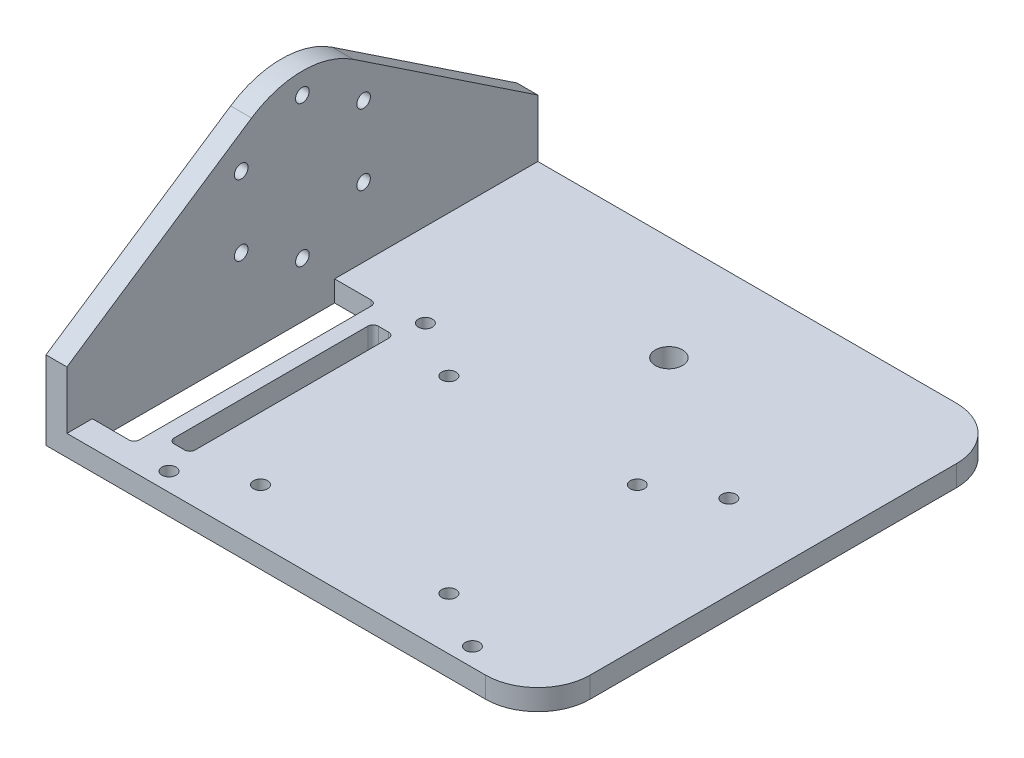
SolidWorks part; units mm, degrees
material "3.1325 (EN-AW 2017A)"
ref_plane "前视基准面" through (0, 0, 0) normal (0, 0, 1) x (1, 0, 0)
ref_plane "上视基准面" through (0, 0, 0) normal (0, 1, 0) x (1, 0, 0)
ref_plane "右视基准面" through (0, 0, 0) normal (1, 0, 0) x (0, 0, -1)
other "Configuration Table"
sketch "草图3" plane through (0, 0, 0) normal (0, 1, 0) x (1, 0, 0)
  line L1 (-45, -45) -> (45, -45)
  line L2 (-45, -45) -> (-45, 45)
  line L3 (-45, 45) -> (45, 45)
  line L4 (45, -45) -> (45, 45)
  line L5 (-45, -45) -> (45, 45) construction
  line L6 (-45, 45) -> (45, -45) construction
  point P0 (0, 0)
  dimension "D1" = 90
  dimension "D2" = 90
extrude "凸台-拉伸3" add sketch "草图3" along normal blind 4
sketch "草图4" plane through (-45, 0, 0) normal (-1, 0, 0) x (0, 0, 1)
  line L1 (-45, 4) -> (45, 4) construction
  line L4 (-45, 4) -> (-45, 15)
  line L5 (-45, 15) -> (-9.7165, 38.5547)
  line L6 (0, -6.9668) -> (0, 45.9026) construction
  line L7 (45, 4) -> (45, 15)
  line L8 (-45, 0) -> (45, 0)
  line L9 (45, 0) -> (45, 4)
  line L10 (45, 4) -> (-45, 4)
  line L11 (-45, 4) -> (-45, 0)
  line L12 (-45, 0) -> (45, 0)
  line L13 (45, 0) -> (45, 4)
  line L15 (-45, 4) -> (-45, 0)
  line L16 (45, 15) -> (9.7165, 38.5547)
  arc A0 (9.7165, 38.5547) -> (-9.7165, 38.5547) centre (0, 24) ccw
  point P16 (-45, 15.4209)
  dimension "D1" = 17.5
  dimension "D2" = 20
  dimension "D4" = 15
  dimension "D3" = 0
extrude "凸台-拉伸4" add sketch "草图4" along normal blind 4
sketch "草图5" plane through (-45, 0, 0) normal (1, 0, 0) x (0, 0, -1)
  arc A0 (9.7165, 38.5547) -> (-9.7165, 38.5547) centre (0, 24) ccw construction
  arc A1 (9.7165, 38.5547) -> (-9.7165, 38.5547) centre (0, 24) ccw construction
  circle A2 centre (0, 37.5) radius 1.3
  circle A3 centre (11.6913, 30.75) radius 1.3
  circle A4 centre (11.6913, 17.25) radius 1.3
  circle A5 centre (0, 10.5) radius 1.3
  circle A6 centre (-11.6913, 17.25) radius 1.3
  circle A7 centre (-11.6913, 30.75) radius 1.3
  point P18 (0, 24)
  dimension "D2" = 2.6
  dimension "D3" = 13.5
  dimension "D1" = 6
extrude "切除-拉伸1" cut sketch "草图5" against normal up to surface (4 mm away) up to face at (-49, 18.3425, 0)
sketch "草图6" plane through (0, 4, 0) normal (0, 1, 0) x (1, 0, 0)
  line L0 (0, 0) -> (0, -64.7291) construction
  line L1 (-29, 7.5) -> (-29, -41.5) construction
  line L2 (-29, -17) -> (29.5377, -17) construction
  line L4 (45, -45) -> (45, 45)
  line L5 (45, 45) -> (-45, 45)
  line L6 (-45, 45) -> (-45, -45)
  line L7 (-45, -45) -> (45, -45)
  line L8 (45, -45) -> (45, 45) construction
  line L9 (45, 45) -> (-45, 45) construction
  line L10 (-45, 45) -> (-45, -45) construction
  line L11 (-45, -45) -> (45, -45) construction
  circle A0 centre (0, 25.05) radius 2.6
  circle A1 centre (-29, -41.5) radius 1.35
  circle A2 centre (-29, 7.5) radius 1.35
  circle A3 centre (-18, -35) radius 1.35
  circle A4 centre (-18, 1) radius 1.35
  circle A5 centre (29, -41.5) radius 1.35
  circle A6 centre (18, -35) radius 1.35
  circle A7 centre (18, 1) radius 1.35
  circle A8 centre (29, 7.5) radius 1.35
  dimension "D2" = 5.2
  dimension "D4" = 2.7
  dimension "D5" = 2.7
  dimension "D7" = 36
  dimension "D8" = 2.7
  dimension "D10" = 36
  dimension "D11" = 58
  dimension "D3" = 19.95
  dimension "D6" = 49
  dimension "D9" = 3.5
  dimension "D1" = 0
extrude "切除-拉伸2" cut sketch "草图6" against normal up to surface (4 mm away) up to face at (-2, 0, 0)
sketch "草图7" plane through (0, 4, 0) normal (0, 1, 0) x (1, 0, 0)
  line L0 (-45, 45) -> (-45, -45) construction
  line L1 (-45, 45) -> (-45, -45) construction
  line L15 (-34, 2.5) -> (-30, 2.5)
  line L16 (-34, 2.5) -> (-34, -36.5)
  line L17 (-34, -36.5) -> (-30, -36.5)
  line L18 (-30, 2.5) -> (-30, -36.5)
  line L19 (-45, -40.15) -> (-37, -40.15)
  line L20 (-45, -40.15) -> (-45, 6.15)
  line L21 (-45, 6.15) -> (-37, 6.15)
  line L22 (-37, -40.15) -> (-37, 6.15)
  circle A0 centre (-29, 7.5) radius 1.35 construction
  circle A1 centre (-29, 7.5) radius 1.35 construction
  circle A2 centre (-29, -41.5) radius 1.35 construction
  circle A3 centre (-29, -41.5) radius 1.35 construction
  circle A12 centre (-18, -35) radius 1.35 construction
  dimension "D2" = 5
  dimension "D4" = 12
  dimension "D1" = 8
  dimension "D3" = 5
  dimension "D5" = 4
  dimension "D6" = 0
extrude "切除-拉伸3" cut sketch "草图7" against normal up to surface (4 mm away) up to face at (0, 0, -27.65)
fillet "圆角3" radius 1 6 edges at (-37, 2, 40.15) (-34, 2, 36.5) (-30, 2, 36.5) (-30, 2, -2.5) (-34, 2, -2.5) (-37, 2, -6.15)
fillet "圆角4" radius 10 2 edges at (45, 2, 45) (45, 2, -45)
